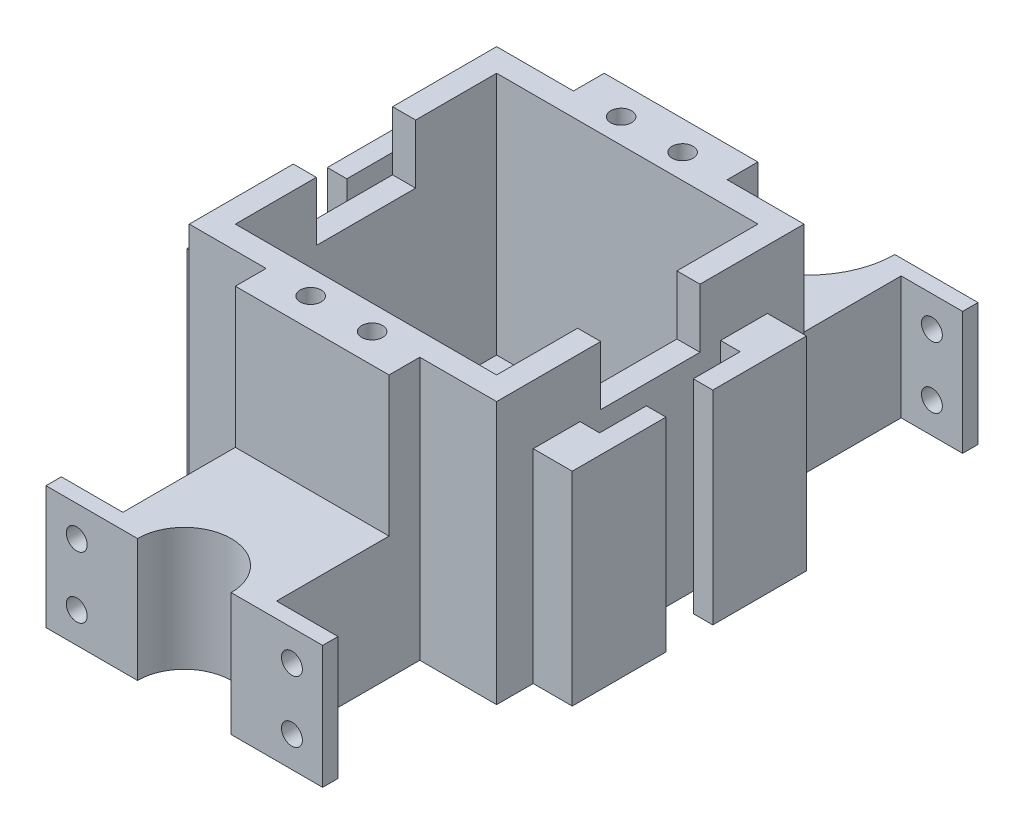
SolidWorks part; units mm, degrees
material "ABS"
ref_plane "Front Plane" through (0, 0, 0) normal (0, 0, 1) x (1, 0, 0)
ref_plane "Top Plane" through (0, 0, 0) normal (0, 1, 0) x (1, 0, 0)
ref_plane "Right Plane" through (0, 0, 0) normal (1, 0, 0) x (0, 0, -1)
sketch "Sketch1" plane through (0, 0, 0) normal (0, 1, 0) x (1, 0, 0)
  line L1 (-21.25, 21.25) -> (21.25, 21.25)
  line L2 (-21.25, 21.25) -> (-21.25, -21.25)
  line L3 (-21.25, -21.25) -> (21.25, -21.25)
  line L4 (21.25, 21.25) -> (21.25, -21.25)
  line L5 (-21.25, 21.25) -> (21.25, -21.25) construction
  line L6 (-21.25, -21.25) -> (21.25, 21.25) construction
  line L7 (-25, 25) -> (25, 25)
  line L8 (-25, 25) -> (-25, -25)
  line L9 (-25, -25) -> (25, -25)
  line L10 (25, 25) -> (25, -25)
  line L11 (-25, 25) -> (25, -25) construction
  line L12 (-25, -25) -> (25, 25) construction
  point P0 (0, 0)
  point P6 (0, 0)
  dimension "D1" = 42.5
  dimension "D2" = 42.5
  dimension "D3" = 50
  dimension "D4" = 50
extrude "Boss-Extrude1" add sketch "Sketch1" along normal blind 3 contours L8 L9 L10 L7
sketch "Sketch3" plane through (0, 3, 0) normal (0, 1, 0) x (1, 0, 0)
  line L1 (-25, 25) -> (25, 25)
  line L2 (-25, 25) -> (-25, -25)
  line L3 (-25, -25) -> (25, -25)
  line L4 (25, 25) -> (25, -25)
  line L5 (-25, 25) -> (25, -25) construction
  line L6 (-25, -25) -> (25, 25) construction
  line L7 (-21.25, 21.25) -> (21.25, 21.25)
  line L8 (-21.25, 21.25) -> (-21.25, -21.25)
  line L9 (-21.25, -21.25) -> (21.25, -21.25)
  line L10 (21.25, 21.25) -> (21.25, -21.25)
  line L11 (-21.25, 21.25) -> (21.25, -21.25) construction
  line L12 (-21.25, -21.25) -> (21.25, 21.25) construction
  point P0 (0, 0)
  point P7 (0, 0)
  dimension "D1" = 42.5
extrude "Boss-Extrude2" add sketch "Sketch3" along normal blind 39.7
sketch "Sketch9" plane through (0, 0, 25) normal (0, 0, 1) x (1, 0, 0)
  line L0 (0, 42.7) -> (0, 0) construction
  line L1 (-12.5, 20) -> (12.5, 20)
  line L2 (-12.5, 20) -> (-12.5, 0)
  line L3 (-12.5, 0) -> (12.5, 0)
  line L4 (12.5, 20) -> (12.5, 0)
  line L5 (-12.5, 20) -> (12.5, 0) construction
  line L6 (-12.5, 0) -> (12.5, 20) construction
  line L7 (-25, 42.7) -> (25, 42.7) construction
  line L8 (-25, 0) -> (25, 0) construction
  line L9 (-7.5, 20) -> (12.5, 20)
  line L12 (12.5, 20) -> (12.5, 15)
  line L17 (-7.5, 0) -> (12.5, 0)
  line L18 (12.5, 5) -> (12.5, 0)
  point P0 (0, 10)
  point P10 (0, 28.85)
  point P15 (0, 13.85)
  point P20 (0, 21.35)
  dimension "D1" = 25
  dimension "D2" = 20
extrude "Boss-Extrude4" add sketch "Sketch9" along normal blind 25.8 contours L3 L2 L1 L4
sketch "Sketch11" plane through (0, 20, 0) normal (0, 1, 0) x (1, 0, 0)
  line L0 (-12.5, -50.8) -> (12.5, -50.8) construction
  circle A0 centre (0, -50.8) radius 7.62
  dimension "D1" = 15.24
extrude "Cut-Extrude1" cut sketch "Sketch11" against normal up to next
sketch "Sketch12" plane through (-12.5, 0, 0) normal (-1, 0, 0) x (0, 0, 1)
  line L0 (50.8, 20) -> (25, 20) construction
  line L1 (48.3, 20) -> (50.8, 20)
  line L2 (48.3, 20) -> (48.3, 0)
  line L3 (48.3, 0) -> (50.8, 0)
  line L4 (50.8, 20) -> (50.8, 0)
  line L5 (48.3, 20) -> (50.8, 0) construction
  line L6 (48.3, 0) -> (50.8, 20) construction
  point P0 (49.55, 10)
  dimension "D1" = 2.5
extrude "Boss-Extrude5" add sketch "Sketch12" along normal blind 10
mirror "Mirror2" about plane through (0, 0, 0) normal (1, 0, 0) of "Boss-Extrude5"
sketch "Sketch13" plane through (0, 0, 50.8) normal (0, 0, 1) x (1, 0, 0)
  line L0 (-22.5, 20) -> (-7.62, 20) construction
  line L1 (-22.5, 0) -> (-22.5, 20) construction
  line L2 (22.5, 0) -> (22.5, 20) construction
  line L3 (7.62, 20) -> (22.5, 20) construction
  line L4 (-22.5, 0) -> (-7.62, 0) construction
  line L5 (7.62, 0) -> (22.5, 0) construction
  line L6 (-22.5, 0) -> (-22.5, 20) construction
  line L7 (22.5, 0) -> (22.5, 20) construction
  circle A0 centre (-17.5, 15) radius 1.7
  circle A1 centre (17.5, 15) radius 1.7
  circle A2 centre (-17.5, 5) radius 1.7
  circle A3 centre (17.5, 5) radius 1.7
  point P0 (-17.5, 15)
  point P1 (17.5, 15)
  dimension "D5" = 3.4
  dimension "D6" = 3.4
  dimension "D7" = 3.4
  dimension "D8" = 3.4
  dimension "D1" = 5
  dimension "D2" = 5
  dimension "D3" = 5
  dimension "D4" = 5
  dimension "D9" = 5
  dimension "D10" = 5
  dimension "D11" = 5
  dimension "D12" = 5
extrude "Cut-Extrude2" cut sketch "Sketch13" against normal up to next contours A2 | A3 | A0 | A1
sketch "Sketch15" plane through (0, 0, -25) normal (0, 0, -1) x (-1, 0, 0)
  line L0 (0, 0) -> (0, 42.7) construction
  line L1 (-17.5, 20) -> (17.5, 20)
  line L2 (-17.5, 20) -> (-17.5, 0)
  line L3 (-17.5, 0) -> (17.5, 0)
  line L4 (17.5, 20) -> (17.5, 0)
  line L5 (-17.5, 20) -> (17.5, 0) construction
  line L6 (-17.5, 0) -> (17.5, 20) construction
  line L7 (25, 0) -> (-25, 0) construction
  line L8 (-25, 42.7) -> (25, 42.7) construction
  point P0 (0, 21.35)
  dimension "D1" = 20
  dimension "D2" = 35
  dimension "D3" = 17.5
extrude "Boss-Extrude6" add sketch "Sketch15" along normal blind 25.8
sketch "Sketch16" plane through (0, 20, 0) normal (0, 1, 0) x (1, 0, 0)
  line L0 (-17.5, 50.8) -> (17.5, 50.8) construction
  circle A0 centre (0, 50.8) radius 13.97
  dimension "D1" = 27.94
extrude "Cut-Extrude3" cut sketch "Sketch16" against normal up to next contours A0
sketch "Sketch17" plane through (-17.5, 0, 0) normal (-1, 0, 0) x (0, 0, 1)
  line L0 (-50.8, 0) -> (-50.8, 20) construction
  line L1 (-48.3, 20) -> (-50.8, 20)
  line L2 (-48.3, 20) -> (-48.3, 0)
  line L3 (-48.3, 0) -> (-50.8, 0)
  line L4 (-50.8, 20) -> (-50.8, 0)
  line L5 (-48.3, 20) -> (-50.8, 0) construction
  line L6 (-48.3, 0) -> (-50.8, 20) construction
  line L7 (-50.8, 0) -> (-25, 0) construction
  line L8 (-50.8, 20) -> (-25, 20) construction
  point P0 (-49.55, 10)
  dimension "D1" = 2.5
extrude "Boss-Extrude7" add sketch "Sketch17" along normal blind 10
mirror "Mirror3" about plane through (0, 0, 0) normal (1, 0, 0) of "Boss-Extrude7"
sketch "Sketch18" plane through (0, 0, -50.8) normal (0, 0, -1) x (-1, 0, 0)
  line L0 (-27.5, 20) -> (-27.5, 0) construction
  line L1 (-27.5, 0) -> (-13.97, 0) construction
  line L2 (13.97, 0) -> (27.5, 0) construction
  line L3 (27.5, 20) -> (27.5, 0) construction
  line L4 (-13.97, 20) -> (-27.5, 20) construction
  line L5 (27.5, 20) -> (13.97, 20) construction
  line L6 (27.5, 20) -> (27.5, 0) construction
  line L7 (-27.5, 20) -> (-27.5, 0) construction
  circle A0 centre (-22.5, 5) radius 1.7
  circle A1 centre (22.5, 5) radius 1.7
  circle A2 centre (-22.5, 15) radius 1.7
  circle A3 centre (22.5, 15) radius 1.7
  dimension "D5" = 3.4
  dimension "D6" = 3.4
  dimension "D7" = 3.4
  dimension "D8" = 3.4
  dimension "D1" = 5
  dimension "D2" = 5
  dimension "D3" = 5
  dimension "D4" = 5
  dimension "D9" = 5
  dimension "D10" = 5
  dimension "D11" = 5
  dimension "D12" = 5
extrude "Cut-Extrude4" cut sketch "Sketch18" against normal up to next contours A2 | A0 | A3 | A1
sketch "Sketch19" plane through (25, 0, 0) normal (1, 0, 0) x (0, 0, -1)
  line L0 (25, 0) -> (-25, 0) construction
  line L5 (-25, 42.7) -> (25, 42.7) construction
  line L11 (-8.075, 42.7) -> (8.075, 42.7)
  line L12 (-8.075, 42.7) -> (-8.075, 33.1)
  line L17 (-8.075, 33.1) -> (8.075, 33.1)
  line L18 (8.075, 42.7) -> (8.075, 33.1)
  point P8 (0, 0)
  point P9 (0, 42.7)
  line M27 (25, 42.7) -> (-25, 42.7)
  dimension "D1" = 16.15
  dimension "D2" = 9.6
extrude "Cut-Extrude5" cut sketch "Sketch19" against normal blind 5 and the other way through all contours L18 L12 L17 M27
sketch "Sketch20" plane through (0, 20, 0) normal (0, 1, 0) x (1, 0, 0)
  line L0 (12.5, -48.3) -> (12.5, -25) construction
  line L1 (-12.5, -30) -> (12.5, -30)
  line L2 (-12.5, -30) -> (-12.5, -25)
  line L3 (-12.5, -25) -> (12.5, -25)
  line L4 (12.5, -30) -> (12.5, -25)
  line L5 (-12.5, -30) -> (12.5, -25) construction
  line L6 (-12.5, -25) -> (12.5, -30) construction
  line L7 (-12.5, -25) -> (12.5, -25) construction
  line L9 (-12.5, 30) -> (12.5, 30)
  line L10 (-12.5, 30) -> (-12.5, 25)
  line L11 (-12.5, 25) -> (12.5, 25)
  line L12 (12.5, 30) -> (12.5, 25)
  line L13 (-12.5, 30) -> (12.5, 25) construction
  line L14 (-12.5, 25) -> (12.5, 30) construction
  line L15 (-17.5, 25) -> (17.5, 25) construction
  point P0 (0, -27.5)
  point P9 (0, 27.5)
  dimension "D1" = 5
  dimension "D2" = 5
  dimension "D3" = 25
  dimension "D4" = 25
extrude "Boss-Extrude8" add sketch "Sketch20" along normal up to surface (22.7 mm away) up to face at (7.7083, 42.7, 0)
sketch "Sketch21" plane through (0, 42.7, 0) normal (0, 1, 0) x (1, 0, 0)
  line L0 (-12.5, -30) -> (12.5, -30) construction
  line L1 (12.5, -30) -> (12.5, -25) construction
  line L2 (-12.5, -25) -> (-12.5, -30) construction
  line L5 (12.5, 30) -> (-12.5, 30) construction
  circle A0 centre (5, -25.25) radius 1.7
  circle A1 centre (-5, 25.25) radius 1.7
  circle A2 centre (5, 25.25) radius 1.7
  circle A3 centre (-5, -25.25) radius 1.7
  dimension "D1" = 3.4
  dimension "D4" = 3.4
  dimension "D7" = 3.4
  dimension "D8" = 3.4
  dimension "D9" = 4.75
  dimension "D2" = 4.75
  dimension "D3" = 7.5
  dimension "D5" = 7.5
  dimension "D6" = 4.75
  dimension "D10" = 4.75
  dimension "D11" = 0
  dimension "D12" = 0
extrude "Cut-Extrude6" cut sketch "Sketch21" against normal blind 10 contours A1 | A2 | A3 | A0
sketch "Sketch23" plane through (-25, 0, 0) normal (-1, 0, 0) x (0, 0, 1)
  line L0 (-25, 0) -> (25, 0) construction
  line L1 (-19.05, 0) -> (19.05, 0)
  line L2 (-19.05, 0) -> (-19.05, 42.7)
  line L3 (-19.05, 42.7) -> (19.05, 42.7)
  line L4 (19.05, 0) -> (19.05, 42.7)
  line L5 (-25, 42.7) -> (25, 42.7) construction
  line L6 (-19.05, 33.09) -> (19.05, 33.09)
  line L7 (-19.05, 42.7) -> (-11.43, 42.7)
  line L8 (-19.05, 42.7) -> (-19.05, 0)
  line L9 (-19.05, 0) -> (-11.43, 0)
  line L10 (-11.43, 42.7) -> (-11.43, 0)
  line L11 (19.05, 42.7) -> (11.43, 42.7)
  line L12 (19.05, 42.7) -> (19.05, 0)
  line L13 (19.05, 0) -> (11.43, 0)
  line L14 (11.43, 42.7) -> (11.43, 0)
  point P8 (0, 42.7)
  point P9 (0, 42.7)
  line M7 (-25, 0) -> (25, 0)
  line M9 (25, 42.7) -> (-25, 42.7)
  dimension "D1" = 38.1
  dimension "D2" = 7.62
  dimension "D3" = 7.62
  dimension "D4" = 9.61
extrude "Boss-Extrude9" add sketch "Sketch23" along normal blind 6.35 contours L10 L3 L2 M7 | L14 L4 M9 M7
sketch "Sketch24" plane through (0, 0, -11.43) normal (0, 0, 1) x (1, 0, 0)
  line L0 (-31.35, 0) -> (-25, 0) construction
  line L1 (-31.35, 33.09) -> (-28.175, 33.09)
  line L2 (-31.35, 33.09) -> (-31.35, 0)
  line L3 (-31.35, 0) -> (-28.175, 0)
  line L4 (-28.175, 33.09) -> (-28.175, 0)
  dimension "D1" = 3.175
extrude "Boss-Extrude10" add sketch "Sketch24" along normal blind 7.62
sketch "Sketch25" plane through (0, 0, 11.43) normal (0, 0, -1) x (-1, 0, 0)
  line L0 (31.35, 0) -> (25, 0) construction
  line L1 (31.35, 33.09) -> (28.175, 33.09)
  line L2 (31.35, 33.09) -> (31.35, 0)
  line L3 (31.35, 0) -> (28.175, 0)
  line L4 (28.175, 33.09) -> (28.175, 0)
extrude "Boss-Extrude11" add sketch "Sketch25" along normal blind 7.62
sketch "Sketch27" plane through (0, 0, 0) normal (0, -1, 0) x (1, 0, 0)
  circle A0 centre (0, 0) radius 11.5
  point P3 (-15.5, 15.55)
  point P4 (15.5, 15.5)
  point P5 (15.5, -15.5)
  point P6 (-15.5, -15.5)
  point P7 (0, 0)
  point P8 (0, 0)
  dimension "D1" = 23
  dimension "D2" = 15.5
  dimension "D3" = 15.55
  dimension "D4" = 15.5
  dimension "D5" = 15.5
  dimension "D6" = 15.5
  dimension "D7" = 15.5
  dimension "D8" = 15.5
  dimension "D9" = 15.5
extrude "Cut-Extrude8" cut sketch "Sketch27" against normal up to next contours A0
sketch "Sketch29" plane through (0, 0, 0) normal (0, -1, 0) x (1, 0, 0)
  point P0 (-15.5, 15.5)
  point P1 (15.5, 15.5)
  point P2 (15.5, -15.5)
  point P3 (-15.5, -15.5)
  dimension "D1" = 15.5
  dimension "D2" = 15.5
  dimension "D3" = 15.5
  dimension "D4" = 15.5
hole_wizard "CSK for M3 Countersunk Flat Head Screw1" positions "3DSketch2" profile "Sketch30" countersink size "M3" standard "ISO" end condition up to next
sketch3d "3DSketch2"
  point P0 (-15.5, 0, 15.5)
  point P3 (15.5, 0, 15.5)
  point P6 (15.5, 0, -15.5)
  point P9 (-15.5, 0, -15.5)
sketch "Sketch30" plane through (-15.5, 0, 15.5) normal (1, 0, 0) x (0, 0, -1)
  line L0 (0, 0) -> (0, 3)
  line L1 (0, 3) -> (1.7, 3)
  line L2 (1.7, 3) -> (1.7, 1.45)
  line L3 (1.7, 1.45) -> (3.15, 0)
  line L5 (3.15, 0) -> (0, 0)
  line L6 (-1.7, 1.45) -> (-3.15, 0) construction
  line L11 (0, -6.35) -> (0, 107.95) construction
  dimension "Thru Hole Dia." = 3.4
  dimension "Thru Hole Depth" = 3
  dimension "Near C'Sink Dia." = 6.3
  dimension "Near C'Sink Angle" = 90
mirror "Mirror4" about plane through (0, 0, 0) normal (1, 0, 0) of "Cut-Extrude5", "Boss-Extrude11", "Boss-Extrude10", "Boss-Extrude9"
